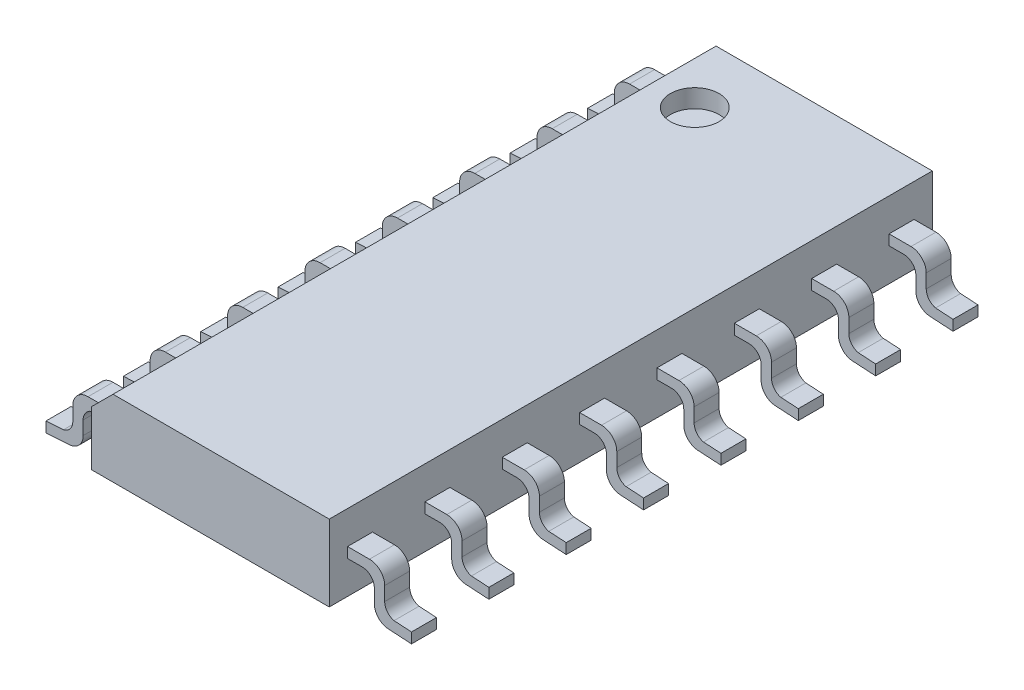
SolidWorks part; units mm, degrees
ref_plane "Plano frontal" through (0, 0, 0) normal (0, 0, 1) x (1, 0, 0)
ref_plane "Plano superior" through (0, 0, 0) normal (0, 1, 0) x (1, 0, 0)
ref_plane "Plano direito" through (0, 0, 0) normal (1, 0, 0) x (0, 0, -1)
ref_plane "Body_Plane" through (0, 0.15, 0) normal (0, 1, 0) x (-1, 0, 0)
sketch "Sketch2" plane through (0, 0.15, 0) normal (0, 1, 0) x (1, 0, 0)
  line L1 (1.95, -4.95) -> (-1.95, -4.95)
  line L2 (1.95, -4.95) -> (1.95, 4.95)
  line L3 (1.95, 4.95) -> (-1.95, 4.95)
  line L4 (-1.95, -4.95) -> (-1.95, 4.95)
  line L5 (1.95, -4.95) -> (-1.95, 4.95) construction
  line L6 (1.95, 4.95) -> (-1.95, -4.95) construction
  point P0 (0, 0)
  dimension "D1" = 9.9
  dimension "D2" = 3.9
extrude "Body" add sketch "Sketch2" along normal blind 1.25
ref_plane "Lead_1_Plane" through (0, 0, 4.445) normal (0, 0, 1) x (1, 0, 0)
sketch "Sketch3" plane through (0, 0, 4.445) normal (0, 0, 1) x (1, 0, 0)
  line L0 (1.95, 1.4) -> (1.95, 0) construction
  line L1 (3, 1.4437) -> (3, 0) construction
  line L2 (1.95, 0.86) -> (2.3102, 0.86)
  line L3 (1.95, 0.69) -> (2.19, 0.69)
  line L4 (2.39, 0.49) -> (2.39, 0.2675)
  line L5 (2.6197, 0.0233) -> (3, 0)
  line L6 (1.95, 0) -> (3, 0) construction
  line L7 (2.56, 0.6102) -> (2.56, 0.3823)
  line L8 (2.7134, 0.1878) -> (3, 0.1703)
  line L9 (3, 0.1703) -> (3, 0)
  line L10 (1.95, 0.69) -> (1.95, 0.86)
  line L11 (2.5364, 0.0284) -> (2.6799, 0.0196) construction
  line L13 (1.95, 1.4) -> (1.95, 0.15) construction
  line L14 (-1.95, 0.15) -> (1.95, 0.15) construction
  arc A0 (2.19, 0.69) -> (2.39, 0.49) centre (2.19, 0.49) cw
  arc A1 (2.39, 0.2675) -> (2.6197, 0.0233) centre (2.6347, 0.2675) ccw
  arc A2 (2.3102, 0.86) -> (2.56, 0.6102) centre (2.3102, 0.6102) cw
  arc A3 (2.56, 0.3823) -> (2.7134, 0.1878) centre (2.76, 0.3823) ccw
  point P8 (2.6197, 0.0233)
  point P21 (1.95, 0.775)
  dimension "D4" = 0.2
  dimension "D3" = 0.2
  dimension "D1" = 1.05
  dimension "D2" = 3.5
  dimension "D5" = 0.61
  dimension "D6" = 0.17
  dimension "D7" = 0.17
  dimension "D8" = 0.085
  dimension "D9" = 0.17
  dimension "D10" = 0.17
  dimension "D11" = 0.17
  dimension "D13" = 0
  dimension "D12" = 0.15
extrude "Lead" add sketch "Sketch3" along normal mid plane 0.41
pattern_linear "SD_Leads" count 8 spacing 1.27 along (0, 0, -1) of "Lead"
mirror "Mirror1" about plane through (0, 0, 0) normal (1, 0, 0) of "SD_Leads", "Lead"
sketch "Sketch4" plane through (0, 1.4, 0) normal (0, 1, 0) x (1, 0, 0)
  line L0 (-1.95, 3.9008) -> (-0.9008, 3.9008) construction
  line L1 (-1.95, 4.95) -> (-1.95, -4.95) construction
  line L2 (-0.9008, 3.9008) -> (-0.9008, 4.95) construction
  line L3 (1.95, 4.95) -> (-1.95, 4.95) construction
  circle A0 centre (-0.9008, 3.9008) radius 0.4
extrude "Cut-Extrude1" cut sketch "Sketch4" against normal blind 0.3
chamfer "Chamfer1" distance 0.35 angle 45 1 edges at (-1.95, 1.4, 0)
equation "\"BODY_X\"= 3.9"
equation "\"BODY_Z\"= 9.9"
equation "\"BODY_THICKNESS\"= 1.25"
equation "\"NUM_LEADS\"= 16"
equation "\"PITCH\"= 1.27"
equation "\"LEAD_WIDTH\"= 0.41"
equation "\"LEAD_THICKNESS\"= 0.17"
equation "\"LEAD_LENGTH\"= 1.05"
equation "\"LEAD_BODY_OFFSET\"= 0.15"
equation "\"D1@Sketch2\" = \"BODY_Z\""
equation "\"D2@Sketch2\" = \"BODY_X\""
equation "\"D6@Sketch3\" = \"LEAD_THICKNESS\""
equation "\"D7@Sketch3\" = \"LEAD_THICKNESS\""
equation "\"D9@Sketch3\" = \"LEAD_THICKNESS\""
equation "\"D10@Sketch3\" = \"LEAD_THICKNESS\""
equation "\"D11@Sketch3\" = \"LEAD_THICKNESS\""
equation "\"D1@Sketch3\" = \"LEAD_LENGTH\""
equation "\"D1@Lead\" = \"LEAD_WIDTH\""
equation "\"LEADS_SIDE\"= \"NUM_LEADS\" / 2"
equation "\"D1@Lead_1_Plane\" = ( \"BODY_Z\" - ( \"LEADS_SIDE\" * \"PITCH\" - \"PITCH\" + \"LEAD_WIDTH\" ) + \"LEAD_WIDTH\" ) / 2"
equation "\"D1@SD_Leads\" = \"LEADS_SIDE\""
equation "\"D3@SD_Leads\" = \"PITCH\""
equation "\"D1@Body\" = \"BODY_THICKNESS\""
equation "\"D12@Sketch3\" = \"LEAD_BODY_OFFSET\""
equation "\"D1@Body_Plane\" = \"LEAD_BODY_OFFSET\""
equation "\"D5@Sketch3\" = ( \"LEAD_LENGTH\" + \"LEAD_THICKNESS\" ) / 2"
